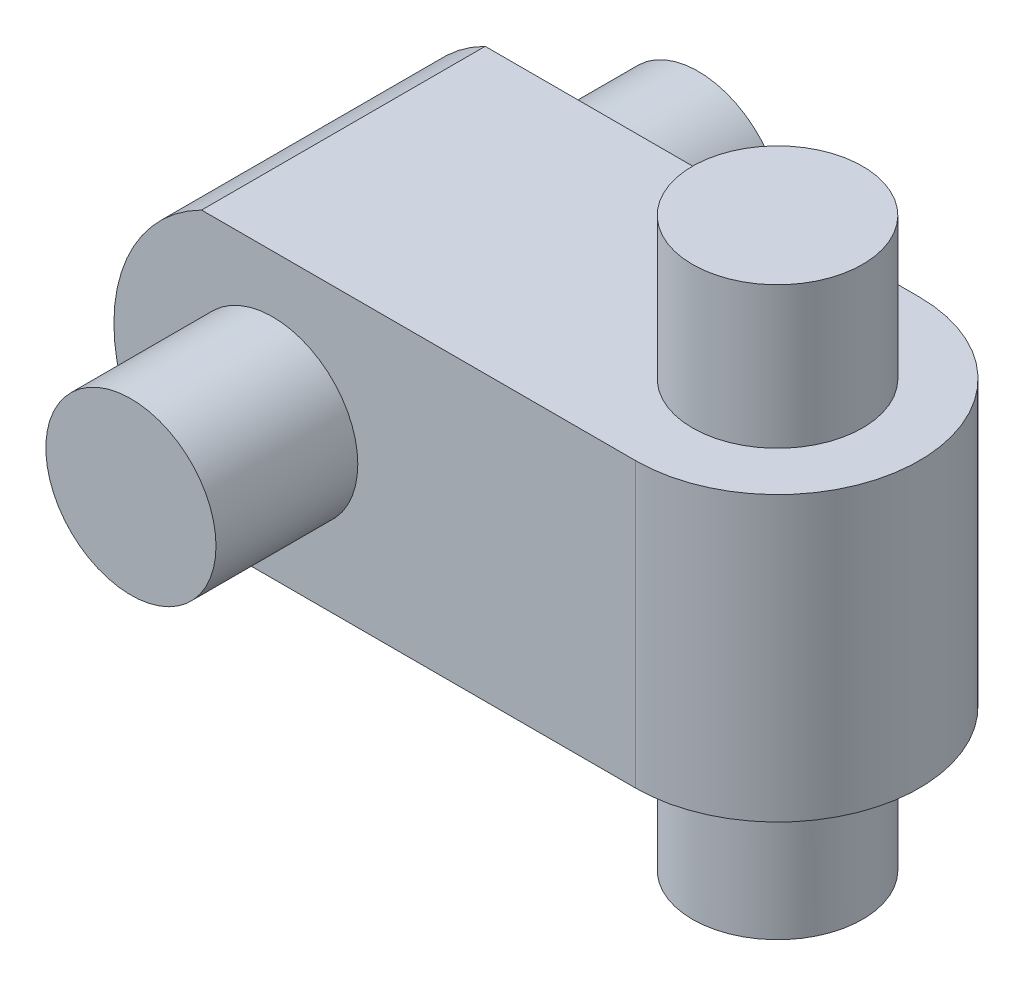
SolidWorks part; units mm, degrees
ref_plane "Alzado" through (0, 0, 0) normal (0, 0, 1) x (1, 0, 0)
ref_plane "Planta" through (0, 0, 0) normal (0, 1, 0) x (1, 0, 0)
ref_plane "Vista lateral" through (0, 0, 0) normal (1, 0, 0) x (0, 0, -1)
sketch "Croquis1" plane through (0, 0, 0) normal (0, 0, 1) x (1, 0, 0)
  line L1 (38.8472, 29.5087) -> (38.8472, 42.0087)
  line L2 (38.8472, 42.0087) -> (-6.1528, 43.5087)
  line L4 (-6.1528, 15.5087) -> (38.8472, 17.0087)
  line L5 (38.8472, 17.0087) -> (38.8472, 29.5087)
  arc A0 (-6.1528, 43.5087) -> (-6.1528, 15.5087) centre (-6.1528, 29.5087) ccw
  dimension "D3" = 28
  dimension "D4" = 45
  dimension "D1" = 25
  dimension "D2" = 12.5
extrude "Saliente-Extruir1" add sketch "Croquis1" along normal blind 25
sketch "Croquis5" plane through (0, 0, 0) normal (0, 1, 0) x (1, 0, 0)
  line L1 (25.8472, 0) -> (38.8472, 0)
  line L2 (38.8472, 0) -> (38.8472, -25)
  line L3 (38.8472, -25) -> (25.8472, -25)
  arc A0 (25.8472, -25) -> (25.8472, 0) centre (25.8472, -12.5) ccw
  dimension "D1" = 13
extrude "Cortar-Extruir1" cut sketch "Croquis5" along normal blind 60 contours A0 L1 L2 L3
sketch "Croquis7" plane through (0, 0, 0) normal (0, 1, 0) x (1, 0, 0)
  line L0 (-6.1528, -12.5) -> (-43.2834, -12.5) construction
  line L1 (-6.1528, -25) -> (-6.1528, 0) construction
ref_plane "Plano1" through (0, 0, 12.5) normal (0, 0, 1) x (1, 0, 0)
sketch "Croquis14" plane through (0, 0, 0) normal (0, 0, 1) x (1, 0, 0)
  line L1 (38.3472, 42.0254) -> (-30.2703, 42.0254)
  line L3 (35.1392, 17.0254) -> (-30.2703, 17.0254)
  line L5 (-30.2703, 17.0254) -> (53.8995, 17.0254)
  line L6 (-30.2703, 17.0254) -> (-30.2703, 4.7645)
  line L7 (-30.2703, 4.7645) -> (53.8995, 4.7645)
  line L8 (53.8995, 17.0254) -> (53.8995, 4.7645)
  line L9 (-30.2703, 42.0254) -> (49.9329, 42.0254)
  line L10 (-30.2703, 42.0254) -> (-30.2703, 48.1396)
  line L11 (-30.2703, 48.1396) -> (49.9329, 48.1396)
  line L12 (49.9329, 42.0254) -> (49.9329, 48.1396)
  dimension "D1" = 25
extrude "Cortar-Extruir2" cut sketch "Croquis14" along normal blind 50 contours L8 L5 L3 L6 L7 | L9 L12 L11 L10 L1
sketch "Croquis15" plane through (0, 0, 0) normal (0, 0, 1) x (1, 0, 0)
  line L0 (-6.1528, 29.5087) -> (-33.5833, 29.5087) construction
ref_plane "Plano3" through (0, 29.5087, 0) normal (0, 1, 0) x (1, 0, 0)
sketch "Croquis16" plane through (0, 29.5087, 0) normal (0, 1, 0) x (1, 0, 0)
  circle A0 centre (25.8472, -12.5) radius 7.5
  dimension "D1" = 15
extrude "Saliente-Extruir4" add sketch "Croquis16" along normal mid plane 50
sketch "Croquis18" plane through (0, 0, 0) normal (0, 1, 0) x (1, 0, 0)
  line L0 (-12.4244, -12.5) -> (-36.3047, -12.5) construction
  line L1 (-12.4244, 0) -> (-12.4244, -25) construction
ref_plane "Plano4" through (0, 0, 12.5) normal (0, 0, 1) x (1, 0, 0)
sketch "Croquis19" plane through (0, 0, 12.5) normal (0, 0, 1) x (1, 0, 0)
  circle A0 centre (-6.1528, 29.5087) radius 7.5
  dimension "D1" = 15
extrude "Saliente-Extruir5" add sketch "Croquis19" along normal mid plane 50
